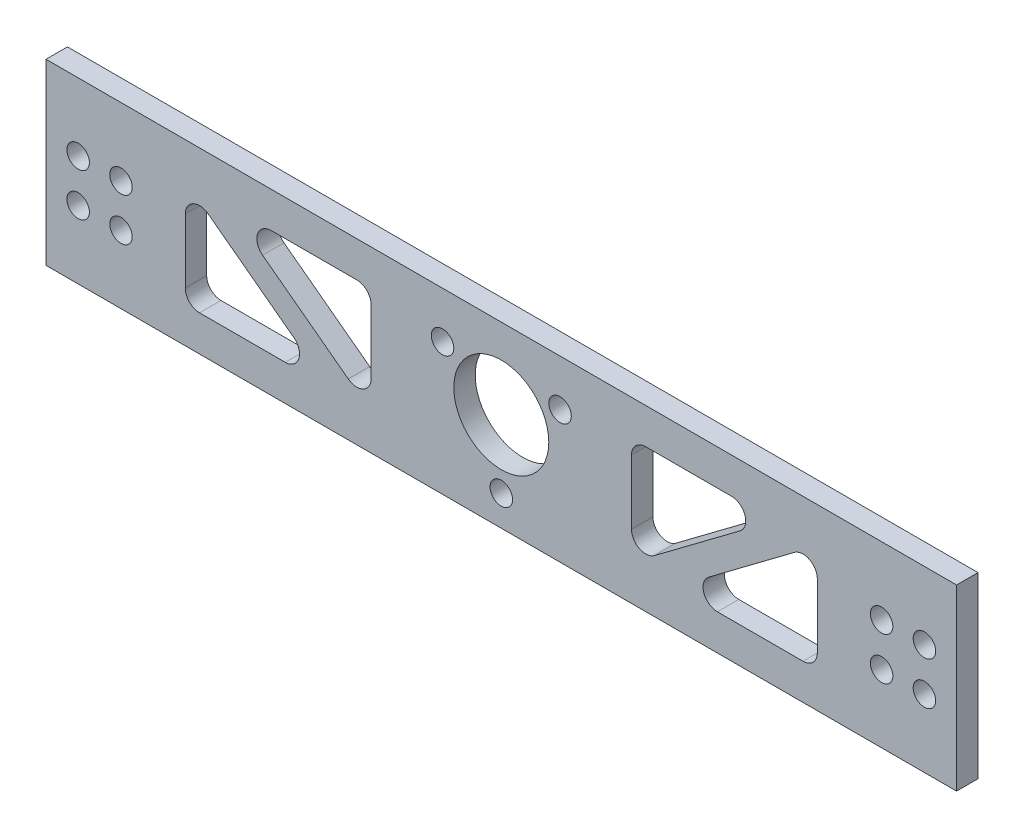
SolidWorks part; units mm, degrees
ref_plane "前视基准面" through (0, 0, 0) normal (0, 0, 1) x (1, 0, 0)
ref_plane "上视基准面" through (0, 0, 0) normal (0, 1, 0) x (1, 0, 0)
ref_plane "右视基准面" through (0, 0, 0) normal (1, 0, 0) x (0, 0, -1)
other "Configuration Table"
sketch "草图1" plane through (0, 0, 0) normal (0, 0, 1) x (1, 0, 0)
  line L1 (0, 0) -> (127.5, 0)
  line L2 (0, 0) -> (0, -25)
  line L3 (0, -25) -> (127.5, -25)
  line L4 (127.5, 0) -> (127.5, -25)
  dimension "D1" = 127.5
  dimension "D2" = 25
extrude "凸台-拉伸1" add sketch "草图1" along normal blind 3
sketch "草图2" plane through (0, 0, 3) normal (0, 0, 1) x (1, 0, 0)
  line L0 (7.5, 0) -> (7.5, -25) construction
  line L1 (127.5, 0) -> (0, 0) construction
  line L2 (0, -25) -> (127.5, -25) construction
  line L3 (63.75, 0) -> (63.75, -25) construction
  line L4 (0, -12.5) -> (7.5, -12.5) construction
  line L5 (0, 0) -> (0, -25) construction
  line L6 (127.5, -12.5) -> (120, -12.5) construction
  line L7 (120, 0) -> (120, -25) construction
  line L9 (63.75, -11.25) -> (55.5228, -6.5) construction
  line L14 (108, -5) -> (108, -20)
  line L15 (108, -20) -> (88, -20)
  line L16 (88, -20) -> (108, -5)
  line L18 (81.9772, -5) -> (81.9772, -20)
  line L19 (81.9772, -20) -> (101.9772, -5)
  line L20 (101.9772, -5) -> (81.9772, -5)
  line L24 (25.5228, -5) -> (45.5228, -5)
  line L25 (45.5228, -20) -> (25.5228, -5)
  line L26 (45.5228, -5) -> (45.5228, -20)
  line L27 (39.5, -20) -> (19.5, -5)
  line L28 (19.5, -20) -> (39.5, -20)
  line L29 (19.5, -5) -> (19.5, -20)
  circle A0 centre (4.5, -9.5) radius 1.575
  circle A1 centre (10.5, -9.5) radius 1.575
  circle A2 centre (10.5, -15.5) radius 1.575
  circle A3 centre (4.5, -15.5) radius 1.575
  circle A4 centre (123, -15.5) radius 1.575
  circle A5 centre (117, -15.5) radius 1.575
  circle A6 centre (117, -9.5) radius 1.575
  circle A7 centre (123, -9.5) radius 1.575
  circle A9 centre (63.75, -11.25) radius 6.65
  circle A10 centre (55.5228, -6.5) radius 1.575
  circle A11 centre (71.9772, -6.5) radius 1.575
  circle A12 centre (63.75, -20.75) radius 1.575
  point P46 (63.75, -11.25)
  dimension "D1" = 3.15
  dimension "D6" = 60
  dimension "D9" = 13.3
  dimension "D11" = 3.15
  dimension "D2" = 3
  dimension "D3" = 3
  dimension "D4" = 20
  dimension "D5" = 7.5
  dimension "D7" = 11.25
  dimension "D8" = 15
  dimension "D10" = 9.5
  dimension "D12" = 15
  dimension "D14" = 20
  dimension "D15" = 5
  dimension "D16" = 5
  dimension "D17" = 12
  dimension "D18" = 10
  dimension "D13" = 3
extrude "切除-拉伸1" cut sketch "草图2" against normal through all
fillet "圆角1" radius 2 12 edges at (88, -20, 1.5) (108, -20, 1.5) (108, -5, 1.5) (81.9772, -5, 1.5) (101.9772, -5, 1.5) (81.9772, -20, 1.5) (45.5228, -5, 1.5) (25.5228, -5, 1.5) (45.5228, -20, 1.5) (39.5, -20, 1.5) (19.5, -5, 1.5) (19.5, -20, 1.5)
